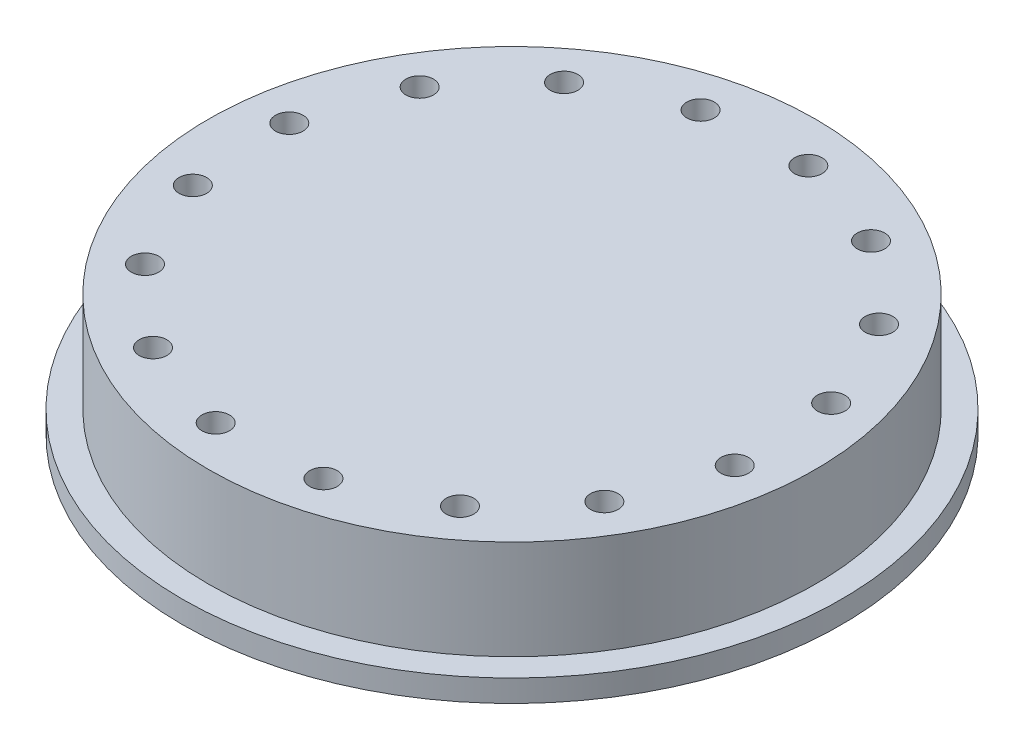
SolidWorks part; units mm, degrees
ref_plane "Front Plane" through (0, 0, 0) normal (0, 0, 1) x (1, 0, 0)
ref_plane "Top Plane" through (0, 0, 0) normal (0, 1, 0) x (1, 0, 0)
ref_plane "Right Plane" through (0, 0, 0) normal (1, 0, 0) x (0, 0, -1)
sketch "Sketch1" plane through (0, 0, 0) normal (0, 1, 0) x (1, 0, 0)
  circle A0 centre (0, 0) radius 29.8611
  dimension "D1" = 59.7222
extrude "Boss-Extrude1" add sketch "Sketch1" along normal mid plane 2
sketch "Sketch2" plane through (0, 1, 0) normal (0, 1, 0) x (1, 0, 0)
  circle A0 centre (0, 0) radius 27.5
  dimension "D1" = 55
extrude "Boss-Extrude2" add sketch "Sketch2" along normal blind 9
sketch "Sketch3" plane through (0, -1, 0) normal (0, -1, 0) x (1, 0, 0)
  circle A0 centre (23.001, -5.9177) radius 1.25 construction
  circle A1 centre (23.5147, 3.3349) radius 1.25 construction
  circle A2 centre (20.4485, 12.0797) radius 1.25 construction
  circle A3 centre (14.2693, 18.9855) radius 1.25 construction
  circle A4 centre (18.9855, -14.2693) radius 1.25 construction
  circle A5 centre (5.9177, 23.001) radius 1.25 construction
  circle A6 centre (-3.3349, 23.5147) radius 1.25 construction
  circle A7 centre (-12.0797, 20.4485) radius 1.25 construction
  circle A8 centre (-18.9855, 14.2693) radius 1.25 construction
  circle A9 centre (-23.001, 5.9177) radius 1.25 construction
  circle A10 centre (-23.5147, -3.3349) radius 1.25 construction
  circle A11 centre (12.0797, -20.4485) radius 1.25 construction
  circle A12 centre (3.3349, -23.5147) radius 1.25 construction
  circle A13 centre (-5.9177, -23.001) radius 1.25 construction
  circle A14 centre (-14.2693, -18.9855) radius 1.25 construction
  circle A15 centre (-20.4485, -12.0797) radius 1.25 construction
  circle A16 centre (23.001, -5.9177) radius 1.25
  circle A17 centre (23.5147, 3.3349) radius 1.25
  circle A18 centre (20.4485, 12.0797) radius 1.25
  circle A19 centre (14.2693, 18.9855) radius 1.25
  circle A20 centre (18.9855, -14.2693) radius 1.25
  circle A21 centre (5.9177, 23.001) radius 1.25
  circle A22 centre (-3.3349, 23.5147) radius 1.25
  circle A23 centre (-12.0797, 20.4485) radius 1.25
  circle A24 centre (-18.9855, 14.2693) radius 1.25
  circle A25 centre (-23.001, 5.9177) radius 1.25
  circle A26 centre (-23.5147, -3.3349) radius 1.25
  circle A27 centre (12.0797, -20.4485) radius 1.25
  circle A28 centre (3.3349, -23.5147) radius 1.25
  circle A29 centre (-5.9177, -23.001) radius 1.25
  circle A30 centre (-14.2693, -18.9855) radius 1.25
  circle A31 centre (-20.4485, -12.0797) radius 1.25
extrude "Cut-Extrude1" cut sketch "Sketch3" against normal through all both and the other way through all
